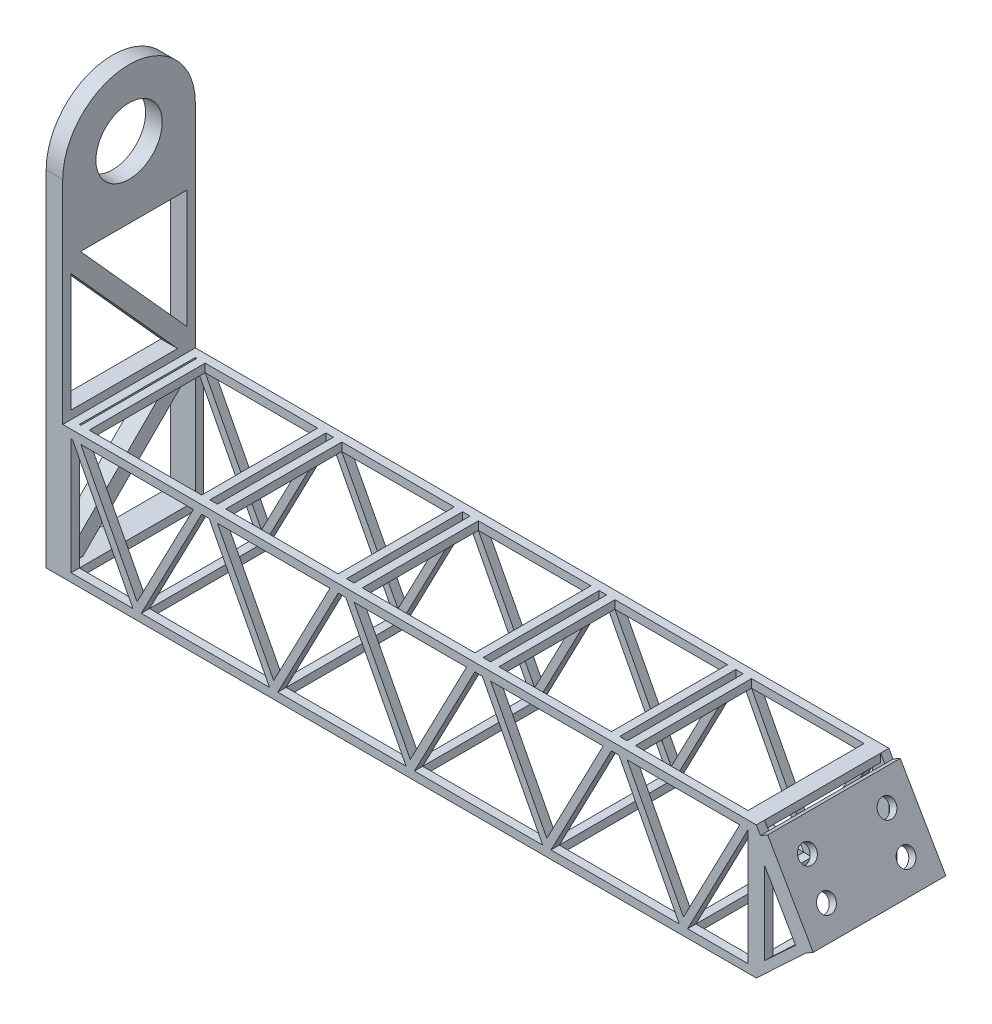
SolidWorks part; units mm, degrees
ref_plane "Front Plane" through (0, 0, 0) normal (0, 0, 1) x (1, 0, 0)
ref_plane "Top Plane" through (0, 0, 0) normal (0, 1, 0) x (1, 0, 0)
ref_plane "Right Plane" through (0, 0, 0) normal (1, 0, 0) x (0, 0, -1)
ref_plane "Plane1" through (0, 0, 12.7) normal (0, 0, 1) x (1, 0, 0)
ref_plane "Plane2" through (-66.421, 0, 0) normal (1, 0, 0) x (0, 0, -1)
sketch "Sketch1" plane through (0, 0, 0) normal (0, 0, 1) x (1, 0, 0)
  line L0 (0, 0) -> (0, 25.4)
  line L1 (0, 25.4) -> (9.525, 8.9022)
  line L2 (9.525, 8.9022) -> (0, 0)
  line L3 (7.5195, 9.2008) -> (1.5875, 3.6566)
  line L4 (1.5875, 3.6566) -> (1.5875, 19.4754)
  line L5 (1.5875, 19.4754) -> (7.5195, 9.2008)
  dimension "D1" = 25.4
  dimension "D2" = 30
  dimension "D3" = 19.05
  dimension "D4" = 1.5875
extrude "Boss-Extrude1" add sketch "Sketch1" along normal blind 1.5875
sketch "Sketch2" plane through (0, 0, 0) normal (-1, 0, 0) x (0, 0, 1)
  line L0 (1.5875, 25.4) -> (1.5875, 0) construction
  line L1 (0, 25.4) -> (1.5875, 25.4)
  line L2 (0, 25.4) -> (0, 23.8125)
  line L3 (0, 23.8125) -> (1.5875, 23.8125)
  line L4 (1.5875, 25.4) -> (1.5875, 23.8125)
  line L6 (0, 0) -> (1.5875, 0)
  line L7 (0, 0) -> (0, 1.5875)
  line L8 (0, 1.5875) -> (1.5875, 1.5875)
  line L9 (1.5875, 0) -> (1.5875, 1.5875)
  dimension "D1" = 1.5875
  dimension "D2" = 1.5875
extrude "Boss-Extrude2" add sketch "Sketch2" along normal blind 132.842
sketch "Sketch3" plane through (-132.842, 0, 0) normal (-1, 0, 0) x (0, 0, 1)
  line L0 (12.7, -55) -> (12.7, 55) construction
  line L1 (0, 25.4) -> (25.4, 25.4)
  line L2 (0, 25.4) -> (0, 0)
  line L3 (0, 0) -> (25.4, 0)
  line L4 (25.4, 25.4) -> (25.4, 0)
  line L5 (1.5875, 23.8125) -> (1.5875, 1.5875)
  line L6 (1.5875, 1.5875) -> (23.8125, 1.5875)
  line L7 (23.8125, 23.8125) -> (23.8125, 1.5875)
  line L8 (1.5875, 23.8125) -> (23.8125, 23.8125)
  point P5 (12.7, 25.4)
  dimension "D1" = 1.5875
extrude "Boss-Extrude3" add sketch "Sketch3" against normal blind 1.5875
mirror "Mirror4" about plane through (0, 0, 12.7) normal (0, 0, 1) of bodies 105
mirror "Mirror5" about plane through (-66.421, 0, 0) normal (1, 0, 0) of "Boss-Extrude3"
sketch "Sketch7" plane through (0, 0, 0) normal (0, 0, -1) x (-1, 0, 0)
  line L0 (-9.525, 8.9022) -> (-8.3344, 7.7894)
  line L1 (-9.525, 8.9022) -> (-8.7102, 10.3136)
  line L2 (-8.3344, 7.7894) -> (-7.5195, 9.2008)
  line L3 (-8.7102, 10.3136) -> (-7.5195, 9.2008)
  line L4 (0, 0) -> (-9.525, 8.9022) construction
  line L5 (-9.525, 8.9022) -> (0, 25.4) construction
extrude "Boss-Extrude4" add sketch "Sketch7" against normal up to surface (22.225 mm away) from surface at -1.5875 starting at face at (0.9071, 12.1575, 1.5875)
sketch "Sketch9" plane through (0, 0, 0) normal (0, 0, -1) x (-1, 0, 0)
  line L0 (1.5875, 23.8125) -> (13.1571, 1.5875)
  line L1 (131.2545, 1.5875) -> (1.5875, 1.5875) construction
  line L2 (13.1571, 1.5875) -> (14.7446, 1.5875)
  line L3 (14.7446, 1.5875) -> (26.3142, 23.8125)
  line L4 (131.2545, 23.8125) -> (1.5875, 23.8125) construction
  line L5 (26.3142, 23.8125) -> (24.7267, 23.8125)
  line L6 (24.7267, 23.8125) -> (13.9509, 3.1123)
  line L7 (13.9509, 3.1123) -> (3.175, 23.8125)
  line L8 (3.175, 23.8125) -> (1.5875, 23.8125)
  dimension "D1" = 1.5875
  dimension "D2" = 1.5875
  dimension "D3" = 1.5875
  dimension "D4" = 55
extrude "Boss-Extrude5" add sketch "Sketch9" against normal blind 1.5875
pattern_linear "LPattern1" count 5 spacing 26.162 along (-1, 0, 0) of "Boss-Extrude5"
mirror "Mirror6" about plane through (0, 0, 12.7) normal (0, 0, 1) of "LPattern1", "Boss-Extrude5"
sketch "Sketch10" plane through (0, 0, 0) normal (0, 0, -1) x (-1, 0, 0)
  line L0 (132.842, 0) -> (0, 0) construction
  line L1 (119.3926, 0) -> (117.8051, 0)
  line L2 (119.3926, 0) -> (119.3926, 1.5875)
  line L3 (119.3926, 1.5875) -> (117.8051, 1.5875)
  line L4 (117.8051, 0) -> (117.8051, 1.5875)
  line L5 (132.842, 25.4) -> (0, 25.4) construction
  line L6 (130.9622, 23.8125) -> (129.3747, 23.8125)
  line L7 (130.9622, 23.8125) -> (130.9622, 25.4)
  line L8 (130.9622, 25.4) -> (129.3747, 25.4)
  line L9 (129.3747, 23.8125) -> (129.3747, 25.4)
  line L11 (107.823, 23.8125) -> (106.2355, 23.8125)
  line L12 (107.823, 23.8125) -> (107.823, 25.4)
  line L13 (107.823, 25.4) -> (106.2355, 25.4)
  line L14 (106.2355, 23.8125) -> (106.2355, 25.4)
  dimension "D1" = 1.5875
  dimension "D2" = 1.5875
  dimension "D3" = 1.5875
extrude "Boss-Extrude6" add sketch "Sketch10" against normal up to surface (22.225 mm away) from surface at -1.5875 starting at face at (-105.5179, 12.7, 1.5875)
pattern_linear "LPattern2" count 5 spacing 26.162 along (1, 0, 0) of "Boss-Extrude6"
sketch "Sketch12" plane through (10.9985, 6.35, 0) normal (0.866, 0.5, 0) x (0, 0, -1)
  line L0 (-25.4, 2.947) -> (-25.4, 21.997) construction
  line L1 (-25.4, 20.4095) -> (0, 20.4095)
  line L2 (-25.4, 20.4095) -> (-25.4, 2.947)
  line L3 (-25.4, 2.947) -> (0, 2.947)
  line L4 (0, 20.4095) -> (0, 2.947)
  dimension "D1" = 17.4625
extrude "Boss-Extrude13" add sketch "Sketch12" along normal blind 1.5875
sketch "Sketch13" plane through (12.3733, 7.1437, 0) normal (0.866, 0.5, 0) x (0, 0, -1)
  line L0 (0, 20.4095) -> (-25.4, 20.4095) construction
  line L1 (-25.4, 20.4095) -> (-25.4, 2.947) construction
  line L2 (-25.4, 2.947) -> (0, 2.947) construction
  line L3 (0, 2.947) -> (0, 20.4095) construction
  point P0 (-20.32, 15.3295)
  point P1 (-5.08, 15.3295)
  point P2 (-5.08, 8.027)
  point P3 (-20.32, 8.027)
  dimension "D1" = 5.08
  dimension "D2" = 5.08
  dimension "D3" = 5.08
  dimension "D4" = 5.08
hole_wizard "M3 Clearance Hole1" positions "Sketch16" profile "Sketch17" hole size "M3" standard "ANSI Metric"
sketch "Sketch16" plane through (12.3733, 7.1437, 0) normal (0.866, 0.5, 0) x (0, 0, -1)
  point P0 (-20.32, 15.3295)
  point P3 (-20.32, 8.027)
  point P6 (-5.08, 15.3295)
  point P9 (-5.08, 8.027)
sketch "Sketch17" plane through (4.7086, 20.4195, 20.32) normal (0, 0, 1) x (-0.5, 0.866, 0)
  line L0 (0, 0) -> (0, 1.5875)
  line L1 (0, 1.5875) -> (1.7, 1.5875)
  line L2 (1.7, 1.5875) -> (1.7, 0)
  line L5 (1.7, 0) -> (0, 0)
  line L11 (0, -6.35) -> (0, 107.95) construction
  dimension "Thru Hole Dia." = 3.4
  dimension "Thru Hole Depth" = 1.5875
sketch "Sketch18" plane through (-132.842, 0, 0) normal (-1, 0, 0) x (0, 0, 1)
  line L0 (12.7, -13.97) -> (12.7, 13.97) construction
  line L1 (25.4, 0) -> (25.4, 25.4) construction
  line L2 (1.5875, 23.8125) -> (1.5875, 14.2875)
  line L3 (1.5875, 23.8125) -> (1.5875, 1.5875) construction
  line L4 (1.5875, 14.2875) -> (5.2472, 14.2875)
  line L5 (1.5875, 23.8125) -> (11.1125, 23.8125)
  line L6 (25.4, 0) -> (25.4, 25.4)
  line L7 (25.4, 25.4) -> (0, 25.4)
  line L8 (0, 25.4) -> (0, 0)
  line L9 (0, 0) -> (25.4, 0)
  line L10 (25.4, 0) -> (25.4, 25.4)
  line L11 (25.4, 25.4) -> (0, 25.4)
  line L12 (0, 25.4) -> (0, 0)
  line L13 (0, 0) -> (25.4, 0)
  line L14 (23.8125, 23.8125) -> (1.5875, 23.8125) construction
  line L15 (11.1125, 23.8125) -> (11.1125, 20.1528)
  line L16 (5.2472, 11.1125) -> (1.5875, 11.1125)
  line L17 (1.5875, 11.1125) -> (1.5875, 1.5875)
  line L18 (1.5875, 1.5875) -> (11.1125, 1.5875)
  line L19 (1.5875, 1.5875) -> (23.8125, 1.5875) construction
  line L20 (11.1125, 1.5875) -> (11.1125, 5.2472)
  line L21 (14.2875, 5.2472) -> (14.2875, 1.5875)
  line L22 (14.2875, 1.5875) -> (23.8125, 1.5875)
  line L23 (23.8125, 1.5875) -> (23.8125, 11.1125)
  line L24 (23.8125, 1.5875) -> (23.8125, 23.8125) construction
  line L25 (23.8125, 11.1125) -> (20.1528, 11.1125)
  line L26 (20.1528, 14.2875) -> (23.8125, 14.2875)
  line L27 (23.8125, 10.3136) -> (23.8125, 24.0252) construction
  line L28 (23.8125, 14.2875) -> (23.8125, 23.8125)
  line L29 (23.8125, 23.8125) -> (14.2875, 23.8125)
  line L30 (14.2875, 23.8125) -> (14.2875, 20.1528)
  arc A0 (11.1125, 20.1528) -> (5.2472, 14.2875) centre (12.7, 12.7) ccw
  arc A1 (20.1528, 14.2875) -> (14.2875, 20.1528) centre (12.7, 12.7) ccw
  arc A2 (5.2472, 11.1125) -> (11.1125, 5.2472) centre (12.7, 12.7) ccw
  arc A3 (14.2875, 5.2472) -> (20.1528, 11.1125) centre (12.7, 12.7) ccw
  circle A4 centre (12.7, 12.7) radius 6.35
  point P6 (25.4, 12.7)
  dimension "D1" = 15.24
  dimension "D7" = 12.7
  dimension "D2" = 0
  dimension "D3" = 3.175
  dimension "D4" = 3.175
  dimension "D5" = 3.175
  dimension "D6" = 3.175
sketch "Sketch19" plane through (0, 0, 0) normal (0, 1, 0) x (1, 0, 0)
  line L0 (-132.842, 0) -> (-136.017, 0)
  line L1 (-132.842, 0) -> (-132.842, -25.4) construction
  line L2 (-136.017, 0) -> (-136.017, -25.4)
  line L3 (-136.017, -25.4) -> (-132.842, -25.4)
  line L4 (-132.842, -25.4) -> (-132.842, 0)
  dimension "D1" = 3.175
extrude "Boss-Extrude14" add sketch "Sketch19" along normal blind 66.04
sketch "Sketch20" plane through (-136.017, 0, 0) normal (-1, 0, 0) x (0, 0, 1)
  line L0 (0, 66.04) -> (25.4, 66.04) construction
  line L1 (25.4, 66.04) -> (25.4, 0) construction
  line L2 (0, 66.04) -> (25.4, 66.04)
  arc A0 (0, 66.04) -> (25.4, 66.04) centre (12.7, 66.04) cw
extrude "Boss-Extrude15" add sketch "Sketch20" against normal up to surface (3.175 mm away) up to face at (-132.842, 45.72, 12.7)
sketch "Sketch21" plane through (-136.017, 0, 0) normal (-1, 0, 0) x (0, 0, 1)
  line L0 (1.5875, 29.7183) -> (21.9989, 52.3875)
  line L1 (1.5875, 1.5875) -> (21.5674, 1.5875)
  line L2 (1.5875, 1.5875) -> (1.5875, 21.5674)
  line L3 (3.8326, 23.8125) -> (23.8125, 23.8125)
  line L4 (23.8125, 3.8326) -> (23.8125, 23.8125)
  line L5 (3.4011, 26.9875) -> (23.8125, 26.9875)
  line L6 (1.5875, 29.7183) -> (1.5875, 52.3875)
  line L7 (1.5875, 52.3875) -> (21.9989, 52.3875)
  line L8 (23.8125, 26.9875) -> (23.8125, 49.6567)
  line L9 (23.8125, 49.6567) -> (3.4011, 26.9875)
  line L10 (1.5875, 21.5674) -> (21.5674, 1.5875)
  line L11 (3.8326, 23.8125) -> (23.8125, 3.8326)
  circle A0 centre (12.7, 66.04) radius 6.35
  point P2 (0, 0)
  point P3 (0, 0)
  point P4 (0, 0)
  dimension "D1" = 12.7
  dimension "D2" = 25.4
  dimension "D4" = 3.175
  dimension "D5" = 3.175
  dimension "D6" = 3.175
  dimension "D7" = 48
  dimension "D8" = 45
extrude "Cut-Extrude1" cut sketch "Sketch21" against normal up to surface (3.175 mm away) up to face at (-132.842, 48.895, 12.7)
